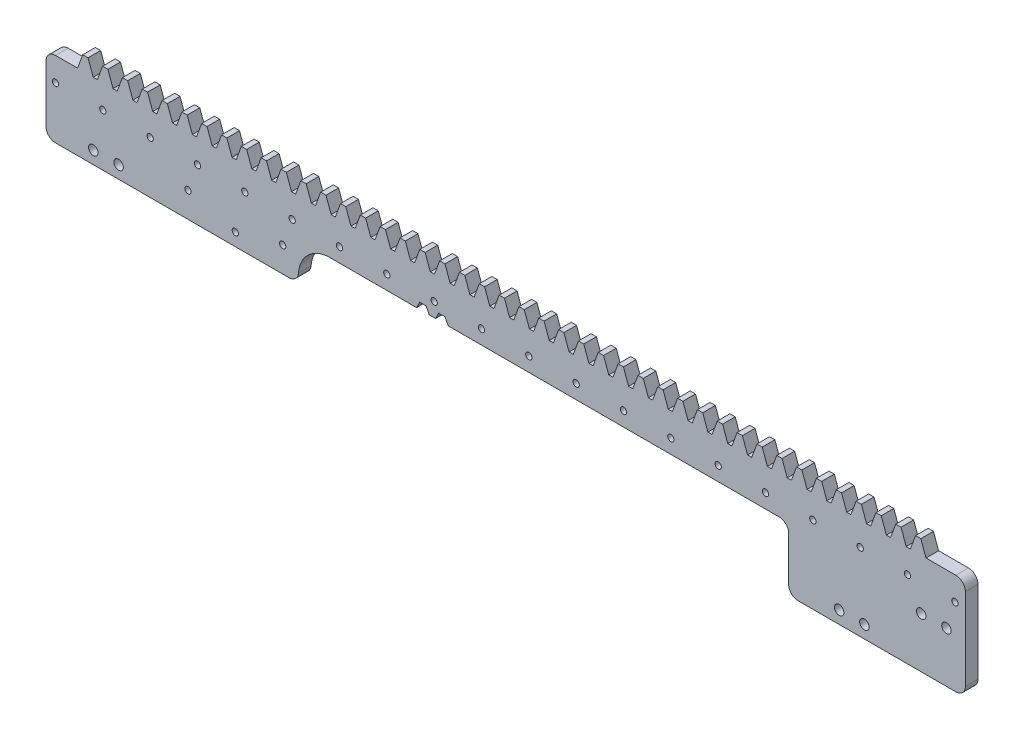
SolidWorks part; units mm, degrees
material "Thornel Mat VMA"
ref_plane "前视基准面" through (0, 0, 0) normal (0, 0, 1) x (1, 0, 0)
ref_plane "上视基准面" through (0, 0, 0) normal (0, 1, 0) x (1, 0, 0)
ref_plane "右视基准面" through (0, 0, 0) normal (1, 0, 0) x (0, 0, -1)
sketch "草图1" plane through (0, 0, 0) normal (0, 0, 1) x (1, 0, 0)
  line L1 (0, 0) -> (271.3274, 0)
  line L2 (0, 0) -> (0, -12)
  line L3 (0, -12) -> (271.3274, -12)
  line L4 (271.3274, 0) -> (271.3274, -12)
  dimension "D1" = 12
  dimension "L" = 271.3274
extrude "拉伸1" add sketch "草图1" along normal blind 4
sketch "草图2" plane through (0, 0, 4) normal (0, 0, 1) x (1, 0, 0)
  line L0 (0, 0) -> (1.6379, 4.5)
  line L1 (1.6379, 4.5) -> (3.3236, 4.5)
  line L2 (3.3236, 4.5) -> (4.9614, 0)
  line L3 (271.3274, 0) -> (0, 0) construction
  line L4 (0, 0) -> (4.9614, 0)
  line L5 (0.9099, 2.5) -> (4.0515, 2.5) construction
  dimension "D2" = 70
  dimension "alpha" = 110
  dimension "ha" = 2
  dimension "hf" = 2.5
  dimension "S" = 3.1416
extrude "拉伸2" add sketch "草图2" against normal up to surface (4 mm away) up to face at (135.6637, -6, 0)
pattern_linear "阵列(线性)1" count 43 spacing 6.2832 along (1, 0, 0) of "拉伸2"
sketch "草图4" plane through (0, 0, 4) normal (0, 0, 1) x (1, 0, 0)
  line L0 (0, -7.5) -> (269.7666, -7.5) construction
  line L1 (0, 0) -> (0, -12) construction
  line L2 (0, -12) -> (271.3274, -12) construction
  circle A0 centre (8, -7.5) radius 1
  circle A1 centre (23, -7.5) radius 1
  circle A2 centre (38, -7.5) radius 1
  circle A3 centre (53, -7.5) radius 1
  circle A4 centre (68, -7.5) radius 1
  circle A5 centre (83, -7.5) radius 1
  circle A6 centre (98, -7.5) radius 1
  circle A7 centre (113, -7.5) radius 1
  circle A8 centre (128, -7.5) radius 1
  circle A9 centre (143, -7.5) radius 1
  circle A10 centre (158, -7.5) radius 1
  circle A11 centre (173, -7.5) radius 1
  circle A12 centre (188, -7.5) radius 1
  circle A13 centre (203, -7.5) radius 1
  circle A14 centre (218, -7.5) radius 1
  circle A15 centre (233, -7.5) radius 1
  circle A16 centre (248, -7.5) radius 1
  circle A17 centre (263, -7.5) radius 1
  dimension "D1" = 2
  dimension "D3" = 15
  dimension "D5" = 8
  dimension "D4" = 4.5
  dimension "D2" = 18
extrude "切除-拉伸1" cut sketch "草图4" against normal blind 10
sketch "草图5" plane through (0, 0, 4) normal (0, 0, 1) x (1, 0, 0)
  line L0 (0, 2.5) -> (271.3274, 2.5) construction
  line L1 (0, 0) -> (0, -12) construction
  line L2 (271.3274, -12) -> (271.3274, 0) construction
  line L3 (3.3236, 4.5) -> (1.6379, 4.5) construction
  dimension "D1" = 2
sketch "草图8" plane through (0, 0, 4) normal (0, 0, 1) x (1, 0, 0)
  line L0 (271.3274, -12) -> (271.3274, -20)
  line L1 (271.3274, -20) -> (225.3274, -20)
  line L2 (225.3274, -20) -> (225.3274, -12)
  line L3 (271.3274, -32) -> (281.3274, -32)
  line L4 (225.3274, -12) -> (271.3274, -12)
  line L5 (271.3274, -16) -> (169.618, -16) construction
  line L6 (225.3274, -20) -> (225.3274, -32)
  line L7 (225.3274, -32) -> (247.3274, -32)
  line L8 (247.3274, -32) -> (247.3274, -20)
  line L9 (205.3274, -28) -> (227.3274, -28) construction
  line L10 (271.3274, -12) -> (271.3274, 0)
  line L11 (271.3274, 0) -> (281.3274, 0)
  line L12 (281.3274, 0) -> (281.3274, -12)
  line L13 (281.3274, -12) -> (271.3274, -12)
  line L14 (271.3274, -20) -> (281.3274, -20)
  line L15 (281.3274, -20) -> (281.3274, -12)
  line L16 (247.3274, -32) -> (271.3274, -32)
  line L17 (271.3274, -32) -> (271.3274, -20)
  line L18 (235.3274, -12) -> (235.3274, -32)
  line L19 (0, -12) -> (0, -24)
  line L20 (0, -24) -> (70, -24)
  line L21 (70, -24) -> (70, -12)
  line L22 (70, -12) -> (0, -12)
  line L23 (0, 0) -> (-10, 0)
  line L24 (-10, 0) -> (-10, -24)
  line L25 (-10, -24) -> (0, -24)
  line L26 (8, -7.5) -> (-18.3003, -7.5) construction
  line L27 (0, 0) -> (0, -12)
  line L29 (281.3274, -32) -> (281.3274, -20)
  line L32 (247.3274, -12) -> (247.3274, -20)
  circle A0 centre (241.3274, -28) radius 1.5
  circle A1 centre (249.3274, -28) radius 1.5
  circle A2 centre (267.3274, -16) radius 1.5
  circle A3 centre (275.3274, -16) radius 1.5
  circle A4 centre (5, -20) radius 1.5
  circle A5 centre (13, -20) radius 1.5
  circle A6 centre (-7, -7.5) radius 1
  circle A7 centre (8, -7.5) radius 1 construction
  circle A8 centre (263, -7.5) radius 1
  circle A9 centre (248, -7.5) radius 1 construction
  circle A10 centre (278, -7.5) radius 1
  circle A11 centre (35, -16) radius 1
  circle A12 centre (40, -1) radius 1
  circle A13 centre (60, -1) radius 1
  circle A14 centre (65, -16) radius 1
  circle A15 centre (50, -20) radius 1
  dimension "D3" = 3
  dimension "D4" = 3
  dimension "D5" = 8
  dimension "D6" = 3
  dimension "D7" = 3
  dimension "D8" = 8
  dimension "D9" = 4
  dimension "D10" = 16
  dimension "D18" = 3
  dimension "D19" = 3
  dimension "D20" = 8
  dimension "D21" = 5
  dimension "D22" = 4
  dimension "D23" = 4
  dimension "D24" = 2
  dimension "D25" = 15
  dimension "D27" = 2
  dimension "D28" = 15
  dimension "D29" = 0
  dimension "D30" = 2
  dimension "D31" = 15
  dimension "D32" = 0
  dimension "D34" = 2
  dimension "D35" = 2
  dimension "D36" = 2
  dimension "D37" = 20
  dimension "D38" = 30
  dimension "D39" = 15
  dimension "D40" = 15
  dimension "D41" = 8
  dimension "D42" = 35
  dimension "D44" = 8
  dimension "D45" = 2
  dimension "D46" = 2
  dimension "D47" = 4
  dimension "D48" = 15
  dimension "D1" = 8
  dimension "D2" = 46
  dimension "D11" = 8
  dimension "D12" = 22
  dimension "D13" = 4
  dimension "D14" = 10
  dimension "D15" = 10
  dimension "D16" = 70
  dimension "D17" = 12
  dimension "D26" = 10
  dimension "D33" = 10
  dimension "D43" = 40
extrude "凸台-拉伸3" add sketch "草图8" against normal blind 4 contours A0 L8 L16 L17 L1 A1 | A2 L0 L14 L15 L13 A3 | L21 L22 L19 L20 | L27 L23 L24 L25 L19 A6 | L4 L32 L1 L0 | L3 L29 L14 L17 | L13 L12 L11 L10 A10 A8 | L1 L18 L7 L8 A0 | L32 L4 L18 L1 | L18 L1 L6 L7 | L18 L4 L2 L1
fillet "圆角3" radius 3 7 edges at (225.3274, -12, 2) (225.3274, -32, 2) (281.3274, 0, 2) (70, -24, 2) (-10, -24, 2) (-10, 0, 2) (281.3274, -32, 2)
fillet "圆角4" radius 10 1 edges at (70, -12, 2)
sketch "草图9" plane through (0, 0, 0) normal (0, 0, -1) x (-1, 0, 0)
  line L0 (-112.4365, 0) -> (-112.4365, -12) construction
  line L1 (-113.0973, 0) -> (-111.7756, 0) construction
  line L2 (-79.9615, -12) -> (-222.3274, -12) construction
  line L6 (-117.4365, -12) -> (-116.4365, -10)
  line L7 (-116.4365, -10) -> (-114.4365, -10)
  line L8 (-114.4365, -10) -> (-113.4365, -12)
  line L9 (-113.4365, -12) -> (-117.4365, -12)
  line L10 (-110.4365, -10) -> (-111.4365, -12)
  line L11 (-108.4365, -10) -> (-110.4365, -10)
  line L12 (-107.4365, -12) -> (-108.4365, -10)
  line L13 (-111.4365, -12) -> (-107.4365, -12)
  dimension "D4" = 2
  dimension "D5" = 2
  dimension "D6" = 4
  dimension "D7" = 4
extrude "切除-拉伸2" cut sketch "草图9" against normal blind 10
equation "\"d\"=\"S@草图2\" * 2"
equation "\"z\"= int(  \"L@草图1\" / (  \"S@草图2\" * 2 ) + 0.5 )"
